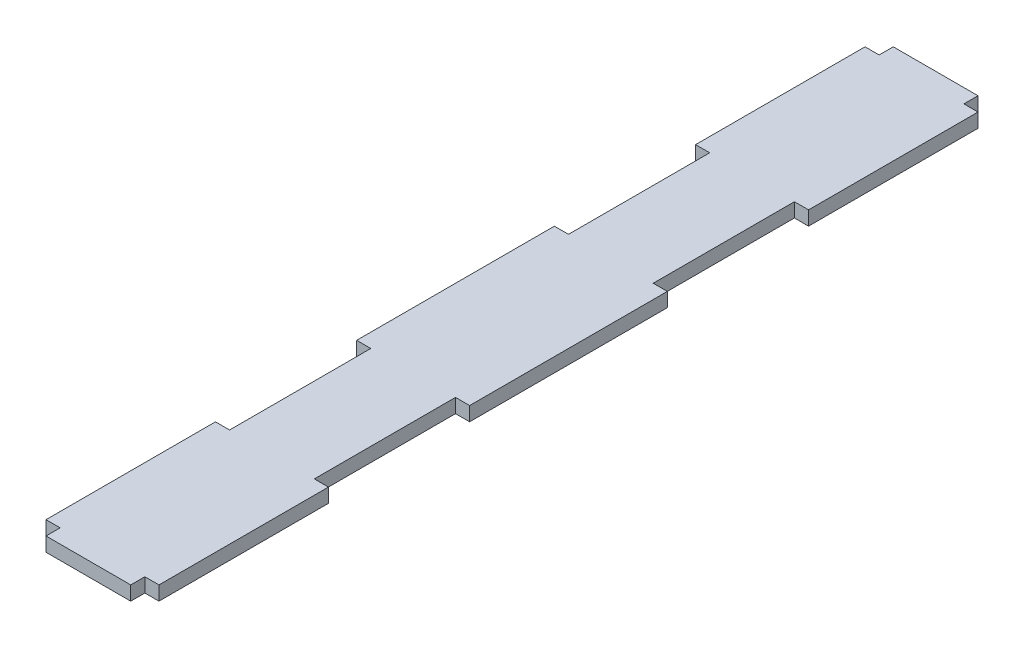
SolidWorks part; units mm, degrees
ref_plane "前视基准面" through (0, 0, 0) normal (0, 0, 1) x (1, 0, 0)
ref_plane "上视基准面" through (0, 0, 0) normal (0, 1, 0) x (1, 0, 0)
ref_plane "右视基准面" through (0, 0, 0) normal (1, 0, 0) x (0, 0, -1)
sketch "草图1" plane through (0, 0, 0) normal (0, 1, 0) x (1, 0, 0)
  line L0 (35, 290) -> (40, 290)
  line L1 (0, 0) -> (5, 0)
  line L2 (0, 0) -> (0, 60)
  line L3 (0, 290) -> (5, 290)
  line L4 (40, 0) -> (40, 60)
  line L5 (0, 230) -> (0, 290)
  line L6 (5, 0) -> (5, -5)
  line L7 (5, -5) -> (35, -5)
  line L8 (35, 0) -> (35, -5)
  line L9 (35, 0) -> (40, 0)
  line L10 (5, 290) -> (5, 295)
  line L11 (5, 295) -> (35, 295)
  line L12 (35, 290) -> (35, 295)
  line L13 (0, 230) -> (5, 230)
  line L14 (40, 230) -> (40, 290)
  line L15 (0, 180) -> (5, 180)
  line L16 (5, 230) -> (5, 180)
  line L17 (0, 110) -> (5, 110)
  line L18 (40, 110) -> (40, 180)
  line L19 (0, 60) -> (5, 60)
  line L20 (5, 110) -> (5, 60)
  line L21 (40, 110) -> (35, 110)
  line L23 (40, 60) -> (35, 60)
  line L24 (35, 110) -> (35, 60)
  line L25 (40, 230) -> (35, 230)
  line L26 (0, 110) -> (0, 180)
  line L27 (40, 180) -> (35, 180)
  line L28 (35, 230) -> (35, 180)
  dimension "D1" = 40
  dimension "D2" = 290
  dimension "D3" = 5
  dimension "D4" = 30
  dimension "D5" = 5
  dimension "D6" = 30
  dimension "D7" = 5
  dimension "D8" = 5
  dimension "D9" = 5
  dimension "D10" = 5
  dimension "D11" = 50
  dimension "D12" = 50
  dimension "D13" = 60
  dimension "D14" = 60
  dimension "D15" = 50
  dimension "D16" = 50
  dimension "D17" = 5
  dimension "D18" = 5
  dimension "D19" = 60
  dimension "D20" = 60
extrude "凸台-拉伸1" add sketch "草图1" along normal blind 5
